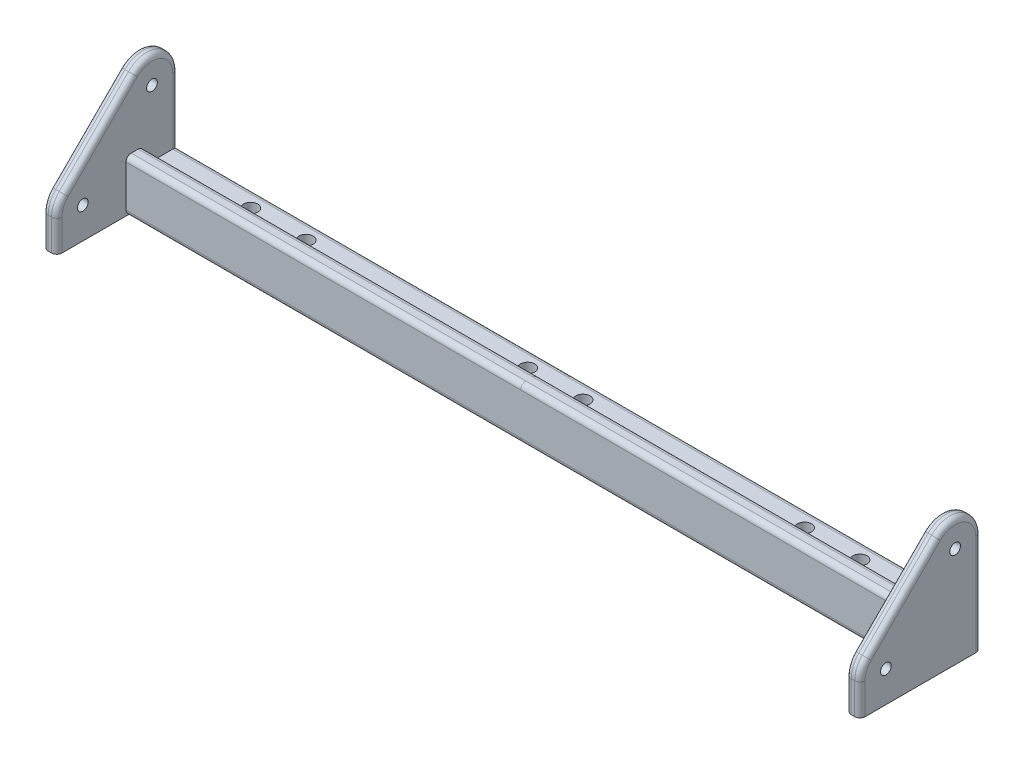
SolidWorks part; units mm, degrees
ref_plane "Plan de face" through (0, 0, 0) normal (0, 0, 1) x (1, 0, 0)
ref_plane "Plan de dessus" through (0, 0, 0) normal (0, 1, 0) x (1, 0, 0)
ref_plane "Plan de droite" through (0, 0, 0) normal (1, 0, 0) x (0, 0, -1)
sketch "Esquisse1" plane through (0, 0, 0) normal (0, 0, 1) x (1, 0, 0)
  line L0 (0, 0) -> (0, 44.2701) construction
  line L1 (0, 0) -> (122.3999, 0) construction
  line L2 (0, 5) -> (122.3999, 5) construction
  line L3 (0, 10) -> (122.3999, 10) construction
  line L4 (0, 0) -> (0, 5) construction
  line L5 (0, 5) -> (15, 5) construction
  line L6 (15, 5) -> (15, 10) construction
  line L7 (15, 10) -> (65, 10) construction
  line L8 (65, 10) -> (65, 5) construction
  line L9 (65, 5) -> (95, 5) construction
  line L10 (95, 5) -> (95, 10) construction
  line L11 (95, 10) -> (114, 10) construction
  line L12 (114, 10) -> (114, 0) construction
  line L13 (114, 0) -> (0, 0) construction
  line L14 (80, 5) -> (80, 10) construction
  line L15 (0, 10) -> (0, 5)
  line L16 (0, 5) -> (15, 5) construction
  line L17 (15, 5) -> (15, 0) construction
  line L18 (15, 0) -> (65, 0) construction
  line L19 (65, 0) -> (65, 5) construction
  line L20 (65, 5) -> (95, 5) construction
  line L21 (95, 5) -> (95, 0) construction
  line L22 (95, 0) -> (114, 0) construction
  line L23 (114, 0) -> (114, 10)
  line L24 (114, 10) -> (0, 10)
  line L25 (0, 5) -> (0, 0)
  line L26 (0, 0) -> (114, 0)
  dimension "D1" = 30
  dimension "D2" = 5
  dimension "D3" = 5
  dimension "D4" = 15
  dimension "D5" = 80
  dimension "D6" = 114
extrude "Boss.-Extru.1" add sketch "Esquisse1" along normal blind 15
sketch "Esquisse2" plane through (114, 0, 0) normal (1, 0, 0) x (0, 0, -1)
  line L0 (0, 0) -> (0, 35.377) construction
  line L1 (0, 0) -> (-43.9624, 0) construction
  line L2 (-36.5, 0) -> (6.4379, 42.9379) construction
  line L3 (1.5, 0) -> (-32.0262, 33.5262) construction
  line L4 (-17.5, 19) -> (20.3247, 19) construction
  line L5 (-17.5, 9) -> (-17.5, 54.8988) construction
  line L8 (-12.8033, 34.3033) -> (-32.8033, 14.3033)
  line L9 (-35, 9) -> (-35, 0)
  line L12 (-35, 0) -> (-15, 0)
  line L13 (0, 29) -> (0, 10)
  line L14 (0, 29) -> (0, 10)
  line L24 (0, 0) -> (0, 10)
  line L25 (0, 10) -> (-15, 10)
  line L26 (-15, 10) -> (-15, 0)
  line L27 (-15, 0) -> (0, 0)
  line L28 (0, 0) -> (0, 10)
  line L29 (0, 10) -> (-15, 10)
  line L30 (-15, 10) -> (-15, 0)
  line L35 (-15, 0) -> (0, 0)
  circle A0 centre (-27.5, 9) radius 1.55
  circle A1 centre (-27.5, 9) radius 10 construction
  circle A2 centre (-7.5, 29) radius 10 construction
  circle A3 centre (-7.5, 29) radius 1.55
  circle A4 centre (-27.5, 9) radius 7.5 construction
  circle A5 centre (-7.5, 29) radius 7.5 construction
  arc A6 (-32.8033, 14.3033) -> (-35, 9) centre (-27.5, 9) ccw
  arc A7 (0, 29) -> (-12.8033, 34.3033) centre (-7.5, 29) ccw
  dimension "D1" = 45
  dimension "D3" = 3.1
  dimension "D4" = 20
  dimension "D5" = 15
  dimension "D7" = 9
  dimension "D2" = 45
  dimension "D6" = 0
extrude "Boss.-Extru.2" add sketch "Esquisse2" along normal blind 4
sketch "Esquisse5" plane through (0, 0, 0) normal (0, -1, 0) x (1, 0, 0)
  line L0 (0, 48.5635) -> (0, -28.5102) construction
  line L1 (-30.4412, 0) -> (140.7754, 0) construction
  line L2 (-6.1805, 5) -> (139.8263, 5) construction
  line L3 (80, 19.9399) -> (80, -9.3402) construction
  line L6 (0, 0) -> (118, 0)
  line L7 (118, 0) -> (118, 35)
  line L8 (118, 35) -> (114, 35)
  line L9 (114, 35) -> (114, 15)
  line L10 (114, 15) -> (0, 15)
  line L11 (0, 15) -> (0, 0)
  line L12 (0, 0) -> (118, 0)
  line L13 (118, 0) -> (118, 35)
  line L14 (118, 35) -> (114, 35)
  line L15 (114, 35) -> (114, 15)
  line L16 (114, 15) -> (0, 15)
  line L17 (0, 15) -> (0, 0)
  circle A0 centre (8, 5) radius 2.05
  circle A1 centre (72, 5) radius 2.05
  circle A2 centre (88, 5) radius 2.05
  dimension "D2" = 8
  dimension "D5" = 4.1
  dimension "D3" = 8
  dimension "D4" = 80
  dimension "D6" = 5
  dimension "D1" = 0
extrude "Enlèv. mat.-Extru.3" cut sketch "Esquisse5" against normal through all contours A0 | A1 | A2
sketch "Esquisse7" plane through (0, 10, 0) normal (0, 1, 0) x (1, 0, 0)
  line L0 (0, -10) -> (114, -10)
  line L4 (114, 0) -> (0, 0)
  line L5 (0, 0) -> (0, -15)
  line L6 (0, -15) -> (114, -15)
  line L7 (114, -15) -> (114, 0)
  line L8 (114, 0) -> (0, 0)
  line L9 (0, 0) -> (0, -15)
  line L10 (0, -15) -> (114, -15)
  line L11 (114, -15) -> (114, 0)
  line M8 (0, 0) -> (0, -15)
  line M9 (0, -15) -> (114, -15)
  line M10 (114, -15) -> (114, 0)
  dimension "D2" = 5
  dimension "D1" = 0
extrude "Boss.-Extru.3" add sketch "Esquisse7" along normal blind 5 contours L0 M8 M9 M10
fillet "Congé1" radius 1.5 15 edges at (57, 10, 10) (57, 10, 0) (57, 15, 10) (57, 15, 15) (57, 0, 15) (118, 14.5, 0) (114, 35.9291, 4.6299) (118, 35.9291, 4.6299) (114, 4.5, 35) (118, 4.5, 35) (114, 11.8701, 34.4291) (118, 11.8701, 34.4291) (114, 19.5, 0) (114, 24.3033, 22.8033) (118, 24.3033, 22.8033)
mirror "Symétrie5" about plane through (0, 5, 15) normal (1, 0, 0) of "Boss.-Extru.1", "Boss.-Extru.2", "Enlèv. mat.-Extru.3", "Boss.-Extru.3", "Congé1"
